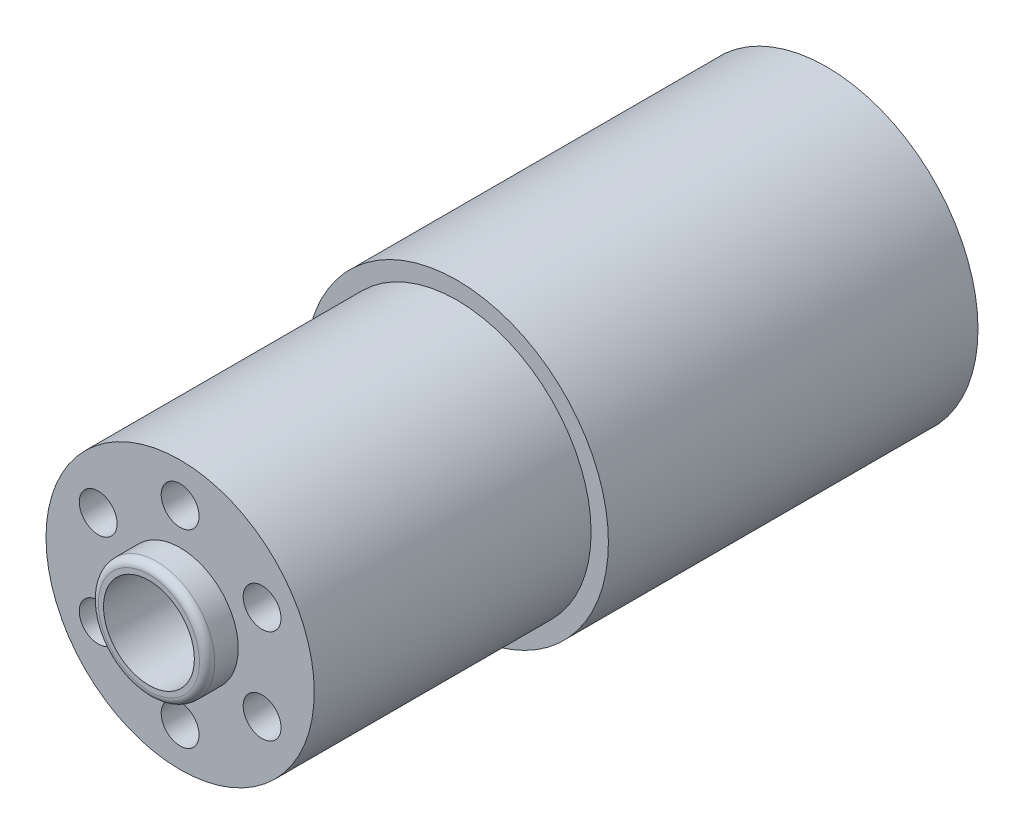
SolidWorks part; units mm, degrees
material "7075-T6, Plate (SS)"
ref_plane "Front Plane" through (0, 0, 0) normal (0, 0, 1) x (1, 0, 0)
ref_plane "Top Plane" through (0, 0, 0) normal (0, 1, 0) x (1, 0, 0)
ref_plane "Right Plane" through (0, 0, 0) normal (1, 0, 0) x (0, 0, -1)
sketch "Sketch1" plane through (0, 0, 0) normal (0, 0, 1) x (1, 0, 0)
  line L0 (0, 0) -> (0, 15.875) construction
  line L1 (0, 15.875) -> (0, 7.62) construction
  line L2 (0, -19.812) -> (0, -25.4) construction
  circle A0 centre (0, 0) radius 7.62
  circle A1 centre (0, 15.875) radius 3.175
  circle A7 centre (0, 0) radius 25.4
  circle A8 centre (13.7482, 7.9375) radius 3.175
  circle A9 centre (13.7482, -7.9375) radius 3.175
  circle A10 centre (0, -15.875) radius 3.175
  circle A11 centre (-13.7482, -7.9375) radius 3.175
  circle A12 centre (-13.7482, 7.9375) radius 3.175
  point P18 (0, -3.048)
  point P22 (0, 0)
  dimension "D1" = 6
  dimension "D2" = 50.8
  dimension "D4" = 6.35
  dimension "D5" = 15.24
  dimension "D3" = 15.875
extrude "Boss-Extrude1" add sketch "Sketch1" along normal blind 108.4402
sketch "Sketch2" plane through (0, 0, 108.4402) normal (0, 0, 1) x (1, 0, 0)
  circle A0 centre (0, 0) radius 7.62
  circle A1 centre (0, 0) radius 9.75
extrude "Boss-Extrude2" add sketch "Sketch2" along normal blind 5.2324
sketch "Sketch3" plane through (0, 0, 0) normal (0, 0, -1) x (-1, 0, 0)
  circle A0 centre (0, 0) radius 7.62
  circle A1 centre (0, 0) radius 9.75
extrude "Boss-Extrude3" add sketch "Sketch3" along normal blind 4.4577
fillet "Fillet2" radius 1.27 1 edges at (-9.75, 0, -4.4577)
fillet "Fillet3" radius 1.27 1 edges at (9.75, 0, 113.6726)
sketch "Sketch4" plane through (0, 0, 0) normal (1, 0, 0) x (0, 0, -1)
  line L0 (0, 0) -> (-129.6168, 0) construction
  line L1 (-108.4402, 25.4) -> (-62, 25.4)
  line L2 (-108.4402, 25.4) -> (-108.4402, 22.5)
  line L3 (-108.4402, 22.5) -> (-62, 22.5)
  line L4 (-62, 25.4) -> (-62, 22.5)
  dimension "D1" = 2.9
  dimension "D2" = 46.4402
revolve "Cut-Revolve1" cut sketch "Sketch4" angle 360 about L0
